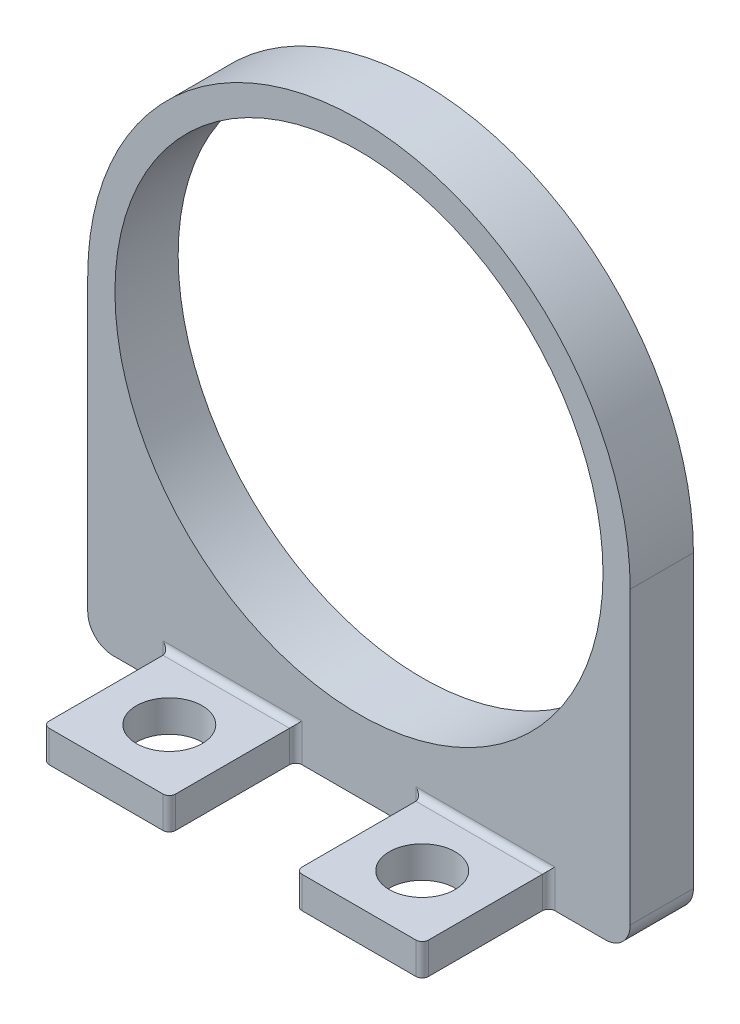
SolidWorks part; units mm, degrees
ref_plane "Front Plane" through (0, 0, 0) normal (0, 0, 1) x (1, 0, 0)
ref_plane "Top Plane" through (0, 0, 0) normal (0, 1, 0) x (1, 0, 0)
ref_plane "Right Plane" through (0, 0, 0) normal (1, 0, 0) x (0, 0, -1)
sketch "Sketch1" plane through (0, 0, 0) normal (0, 0, 1) x (1, 0, 0)
  line L0 (-27.2415, 0) -> (-27.2415, -31.75)
  line L1 (-27.2415, -31.75) -> (27.2415, -31.75)
  line L2 (27.2415, -31.75) -> (27.2415, 0)
  arc A0 (27.2415, 0) -> (-27.2415, 0) centre (0, 0) ccw
  circle A1 centre (0, 0) radius 24.511
  dimension "D1" = 27.2415
  dimension "D3" = 49.022
  dimension "D2" = 31.75
extrude "Boss-Extrude1" add sketch "Sketch1" along normal blind 6.35
sketch "Sketch2" plane through (27.2415, 0, 0) normal (1, 0, 0) x (0, 0, -1)
  line L0 (-6.35, 0) -> (0, 0) construction
  line L1 (-9.525, -3.175) -> (3.175, -3.175)
  line L2 (-9.525, -3.175) -> (-9.525, 3.175)
  line L3 (-9.525, 3.175) -> (3.175, 3.175)
  line L4 (3.175, -3.175) -> (3.175, 3.175)
  line L5 (-9.525, -3.175) -> (3.175, 3.175) construction
  line L6 (-9.525, 3.175) -> (3.175, -3.175) construction
  point P0 (-3.175, 0)
  dimension "D1" = 6.35
sketch "Sketch6" plane through (0, -31.75, 0) normal (0, -1, 0) x (-1, 0, 0)
  line L0 (0, -6.35) -> (0, 0) construction
  line L1 (27.2415, -6.35) -> (-27.2415, -6.35) construction
  line L2 (27.2415, 0) -> (-27.2415, 0) construction
  line L3 (-19.05, -19.05) -> (-6.35, 0) construction
  line L4 (19.05, 0) -> (6.35, 0)
  line L5 (19.05, 0) -> (19.05, -19.05)
  line L6 (19.05, -19.05) -> (6.35, -19.05)
  line L7 (6.35, 0) -> (6.35, -19.05)
  line L8 (19.05, 0) -> (6.35, -19.05) construction
  line L9 (19.05, -19.05) -> (6.35, 0) construction
  line L10 (-19.05, 0) -> (-6.35, -19.05) construction
  line L11 (-6.35, 0) -> (-6.35, -19.05)
  line L12 (-19.05, -19.05) -> (-6.35, -19.05)
  line L13 (-19.05, 0) -> (-19.05, -19.05)
  line L14 (-19.05, 0) -> (-6.35, 0)
  line L15 (27.2415, 0) -> (-27.2415, 0) construction
  line L16 (-27.2415, -6.35) -> (27.2415, -6.35) construction
  point P6 (12.7, -9.525)
  point P15 (-12.7, -9.525)
  dimension "D1" = 12.7
  dimension "D2" = 12.7
  dimension "D3" = 12.7
extrude "Boss-Extrude3" add sketch "Sketch6" against normal blind 3.175
sketch "Sketch7" plane through (0, -28.575, 0) normal (0, 1, 0) x (1, 0, 0)
  line L0 (-19.05, -12.7) -> (-6.35, -12.7) construction
  line L1 (-19.05, -19.05) -> (-19.05, -6.35) construction
  line L2 (-6.35, -6.35) -> (-6.35, -19.05) construction
  line L3 (6.35, -12.7) -> (19.05, -12.7) construction
  line L4 (6.35, -19.05) -> (6.35, -6.35) construction
  line L5 (19.05, -6.35) -> (19.05, -19.05) construction
  circle A0 centre (-12.7, -12.7) radius 3.302
  circle A1 centre (12.7, -12.7) radius 3.302
  dimension "D1" = 6.604
  dimension "D2" = 6.604
extrude "Cut-Extrude5" cut sketch "Sketch7" against normal through all
fillet "Fillet2" radius 0.635 10 edges at (6.35, -30.1625, 6.35) (12.7, -28.575, 6.35) (19.05, -30.1625, 6.35) (19.05, -30.1625, 19.05) (6.35, -30.1625, 19.05) (-6.35, -30.1625, 6.35) (-12.7, -28.575, 6.35) (-19.05, -30.1625, 6.35) (-19.05, -30.1625, 19.05) (-6.35, -30.1625, 19.05)
fillet "Fillet3" radius 2.54 2 edges at (-27.2415, -31.75, 3.175) (27.2415, -31.75, 3.175)
